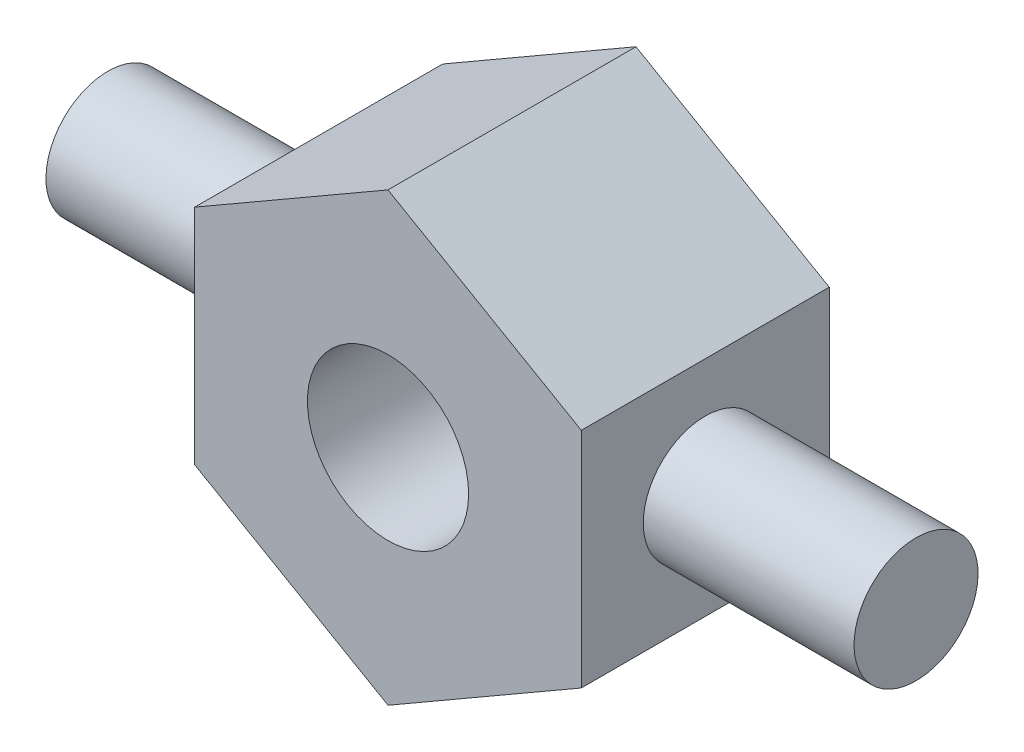
SolidWorks part; units mm, degrees
ref_plane "Front Plane" through (0, 0, 0) normal (0, 0, 1) x (1, 0, 0)
ref_plane "Top Plane" through (0, 0, 0) normal (0, 1, 0) x (1, 0, 0)
ref_plane "Right Plane" through (0, 0, 0) normal (1, 0, 0) x (0, 0, -1)
sketch "Sketch1" plane through (0, 0, 0) normal (0, 0, 1) x (1, 0, 0)
  line L0 (0, 0) -> (63195.8981, 0) construction
  line L1 (0, 0) -> (0, -63195.8981) construction
  line L4 (0, -90) -> (77.9423, -45)
  line L5 (77.9423, -45) -> (77.9423, 45)
  line L6 (77.9423, 45) -> (0, 90)
  line L7 (0, 90) -> (-77.9423, 45)
  line L8 (-77.9423, 45) -> (-77.9423, -45)
  line L9 (-77.9423, -45) -> (0, -90)
  circle A0 centre (0, 0) radius 32.5
  circle A1 centre (0, 0) radius 77.9423 construction
  dimension "D1" = 65
  dimension "D2" = 180
extrude "Boss-Extrude1" add sketch "Sketch1" along normal blind 100
sketch "Sketch2" plane through (77.9423, 0, 0) normal (1, 0, 0) x (0, 0, -1)
  circle A0 centre (-50, 0) radius 25
extrude "Boss-Extrude2" add sketch "Sketch2" along normal blind 85
cosmetic thread "Cosmetic Thread2" parameters "D1"=70, "D2"=42.516
sketch "Sketch3" plane through (-77.9423, 0, 0) normal (-1, 0, 0) x (0, 0, 1)
  circle A0 centre (50, 0) radius 25
extrude "Boss-Extrude3" add sketch "Sketch3" along normal blind 85
cosmetic thread "Cosmetic Thread1" parameters "D1"=70, "D2"=42.516
